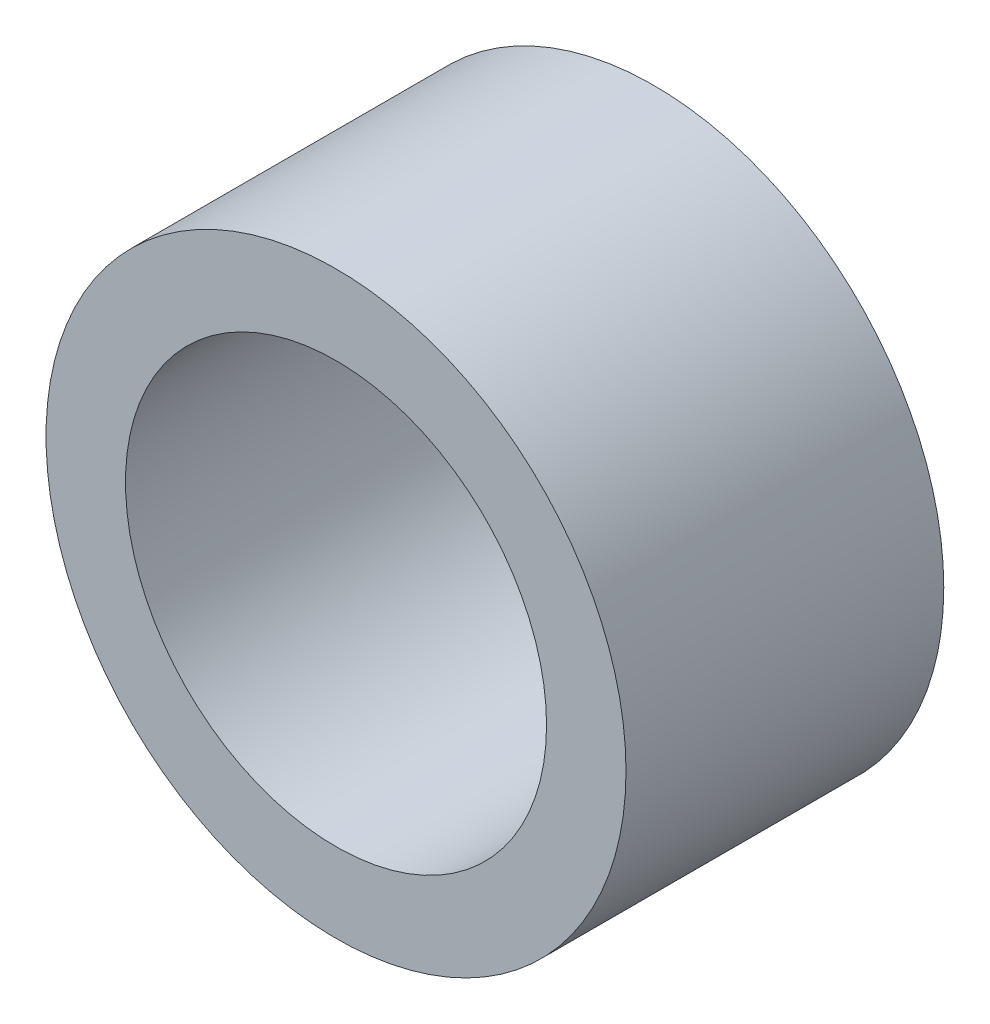
SolidWorks part; units mm, degrees
ref_plane "Plan de face" through (0, 0, 0) normal (0, 0, 1) x (1, 0, 0)
ref_plane "Plan de dessus" through (0, 0, 0) normal (0, 1, 0) x (1, 0, 0)
ref_plane "Plan de droite" through (0, 0, 0) normal (1, 0, 0) x (0, 0, -1)
sketch "Esquisse1" plane through (0, 0, 0) normal (0, 0, 1) x (1, 0, 0)
  circle A0 centre (0, 0) radius 7.3
  circle A1 centre (0, 0) radius 5.3
  dimension "D1" = 10.6
  dimension "D2" = 14.6
extrude "Boss.-Extru.1" add sketch "Esquisse1" along normal blind 8
